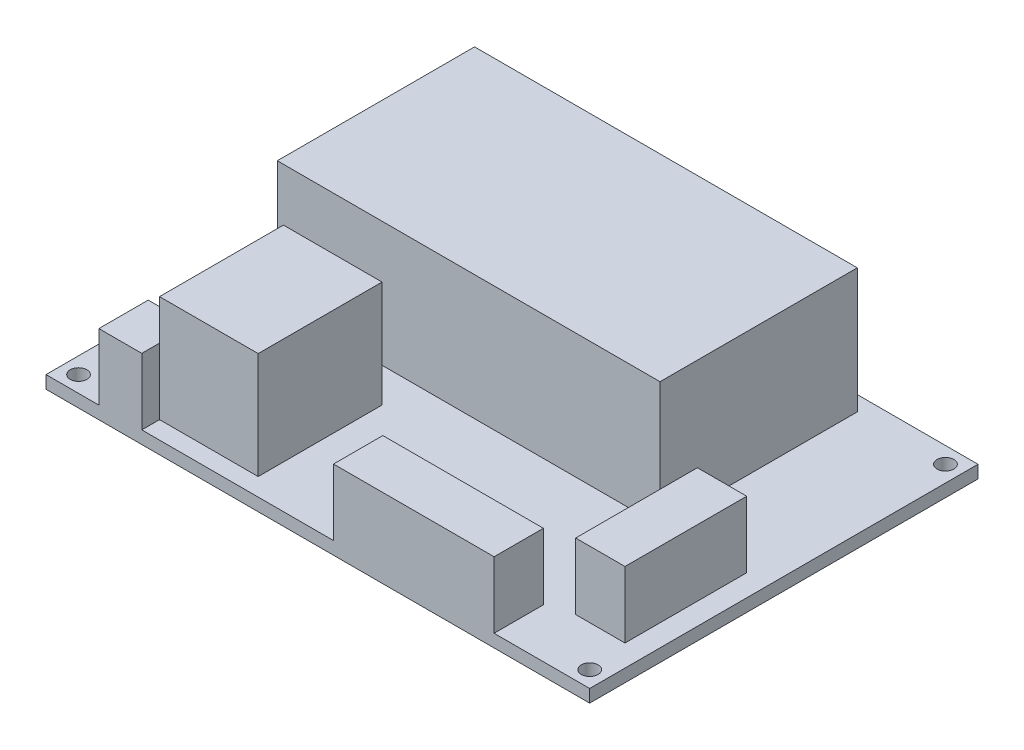
SolidWorks part; units mm, degrees
ref_plane "Front Plane" through (0, 0, 0) normal (0, 0, 1) x (1, 0, 0)
ref_plane "Top Plane" through (0, 0, 0) normal (0, 1, 0) x (1, 0, 0)
ref_plane "Right Plane" through (0, 0, 0) normal (1, 0, 0) x (0, 0, -1)
sketch "Sketch1" plane through (0, 0, 0) normal (0, 1, 0) x (1, 0, 0)
  line L1 (0, 0) -> (70, 0)
  line L2 (0, 0) -> (0, 50)
  line L3 (0, 50) -> (70, 50)
  line L4 (70, 0) -> (70, 50)
  dimension "D1" = 70
  dimension "D2" = 50
extrude "Boss-Extrude1" add sketch "Sketch1" along normal blind 1.6383
sketch "Sketch3" plane through (0, 1.6383, 0) normal (0, 1, 0) x (1, 0, 0)
  line L0 (0, 50) -> (0, 0) construction
  line L1 (0, 0) -> (70, 0) construction
  circle A0 centre (2.0955, 2.0955) radius 1.0795
  dimension "D1" = 2.0955
  dimension "D2" = 2.0955
  dimension "D3" = 2.159
extrude "Cut-Extrude2" cut sketch "Sketch3" against normal through all
ref_plane "Plane3" through (35, 0, 0) normal (1, 0, 0) x (0, 0, -1)
ref_plane "Plane4" through (0, 0, -25) normal (0, 0, 1) x (1, 0, 0)
mirror "Mirror1" about plane through (0, 0, -25) normal (0, 0, 1) of "Cut-Extrude2"
mirror "Mirror2" about plane through (35, 0, 0) normal (1, 0, 0) of "Mirror1", "Cut-Extrude2"
sketch "Sketch4" plane through (0, 1.6383, 0) normal (0, 1, 0) x (1, 0, 0)
  line L0 (70, 0) -> (70, 50) construction
  line L1 (67.206, 23.0124) -> (60.856, 23.0124)
  line L2 (67.206, 23.0124) -> (67.206, 7.3406)
  line L3 (67.206, 7.3406) -> (60.856, 7.3406)
  line L4 (60.856, 23.0124) -> (60.856, 7.3406)
  line L5 (57.6937, 6.35) -> (37.0181, 6.35)
  line L6 (57.6937, 6.35) -> (57.6937, 0)
  line L7 (57.6937, 0) -> (37.0181, 0)
  line L8 (37.0181, 6.35) -> (37.0181, 0)
  line L9 (12.3317, 6.35) -> (6.8072, 6.35)
  line L10 (12.3317, 6.35) -> (12.3317, 0)
  line L11 (12.3317, 0) -> (6.8072, 0)
  line L12 (6.8072, 6.35) -> (6.8072, 0)
  line L13 (0, 0) -> (70, 0) construction
  line L14 (0, 50) -> (0, 0) construction
  dimension "D1" = 6.35
  dimension "D2" = 15.6718
  dimension "D3" = 20.6756
  dimension "D4" = 5.5245
  dimension "D5" = 12.3063
  dimension "D6" = 7.3406
  dimension "D7" = 2.794
  dimension "D8" = 6.8072
extrude "Boss-Extrude2" add sketch "Sketch4" along normal blind 8.5344
sketch "Sketch5" plane through (0, 1.6383, 0) normal (0, 1, 0) x (1, 0, 0)
  line L0 (12.3317, 0) -> (12.3317, 6.35) construction
  line L1 (12.3317, 2.286) -> (25.0317, 2.286)
  line L2 (12.3317, 2.286) -> (12.3317, 18.2372)
  line L3 (12.3317, 18.2372) -> (25.0317, 18.2372)
  line L4 (25.0317, 2.286) -> (25.0317, 18.2372)
  line L5 (12.3317, 0) -> (37.0181, 0) construction
  dimension "D1" = 2.286
  dimension "D2" = 15.9512
  dimension "D3" = 12.7
extrude "Boss-Extrude3" add sketch "Sketch5" along normal blind 13.716
sketch "Sketch7" plane through (0, 1.6383, 0) normal (0, 1, 0) x (1, 0, 0)
  line L0 (0, 50) -> (0, 0) construction
  line L1 (56.388, 48.0696) -> (7.112, 48.0696)
  line L2 (56.388, 48.0696) -> (56.388, 22.6696)
  line L3 (56.388, 22.6696) -> (7.112, 22.6696)
  line L4 (7.112, 48.0696) -> (7.112, 22.6696)
  line L5 (70, 50) -> (0, 50) construction
  dimension "D1" = 7.112
  dimension "D2" = 25.4
  dimension "D3" = 49.276
  dimension "D4" = 1.9304
extrude "Boss-Extrude4" add sketch "Sketch7" along normal blind 16.0655
